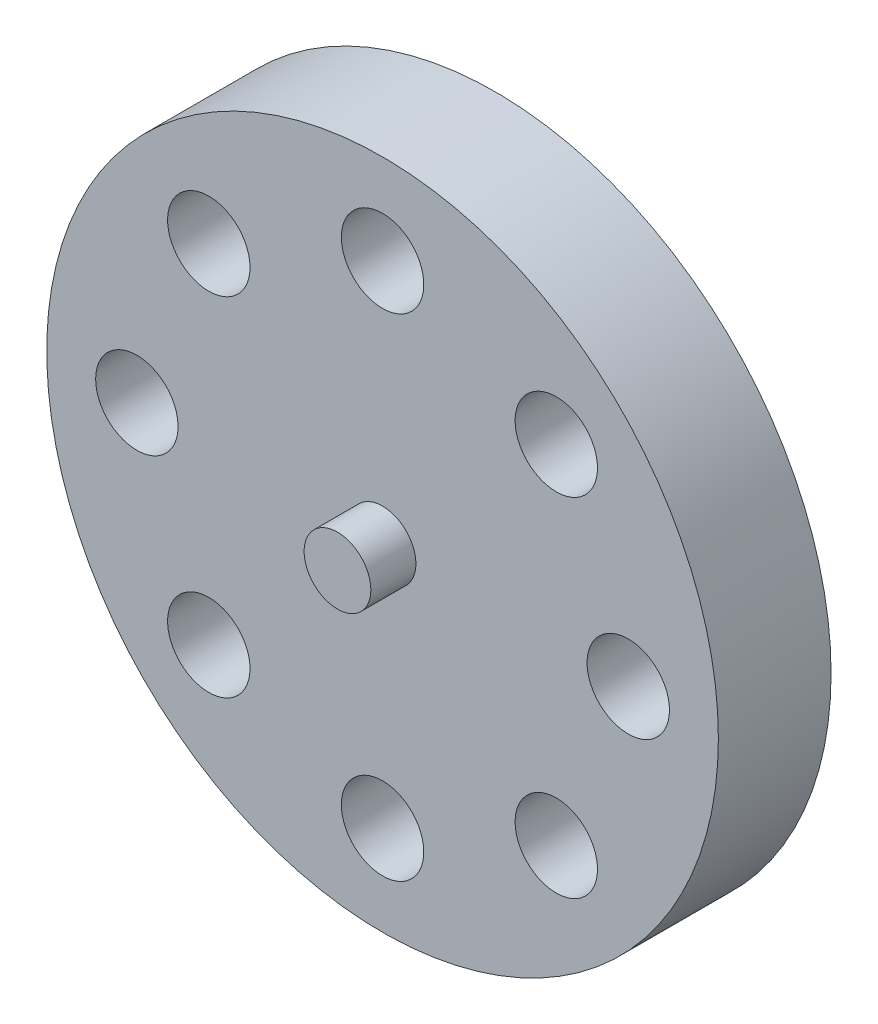
SolidWorks part; units mm, degrees
ref_plane "Front Plane" through (0, 0, 0) normal (0, 0, 1) x (1, 0, 0)
ref_plane "Top Plane" through (0, 0, 0) normal (0, 1, 0) x (1, 0, 0)
ref_plane "Right Plane" through (0, 0, 0) normal (1, 0, 0) x (0, 0, -1)
sketch "Sketch1" plane through (0, 0, 0) normal (0, 0, 1) x (1, 0, 0)
  circle A0 centre (0, 0) radius 37.8431
extrude "Boss-Extrude1" add sketch "Sketch1" along normal blind 12.7
sketch "Sketch2" plane through (0, 0, 12.7) normal (0, 0, 1) x (1, 0, 0)
  circle A0 centre (0, 0) radius 3.7595
  circle A1 centre (28.8059, 0) radius 3.5227
extrude "Boss-Extrude2" add sketch "Sketch2" along normal blind 5.08 contours A0
sketch "Sketch4" plane through (0, 0, 12.7) normal (0, 0, 1) x (1, 0, 0)
  circle A0 centre (27.6882, 0) radius 4.6429
extrude "Cut-Extrude1" cut sketch "Sketch4" against normal through all contours A0
pattern_circular "CirPattern1" count 8 over 360 about axis through (0, 0, 0) along (0, 0, 1) of "Cut-Extrude1"
